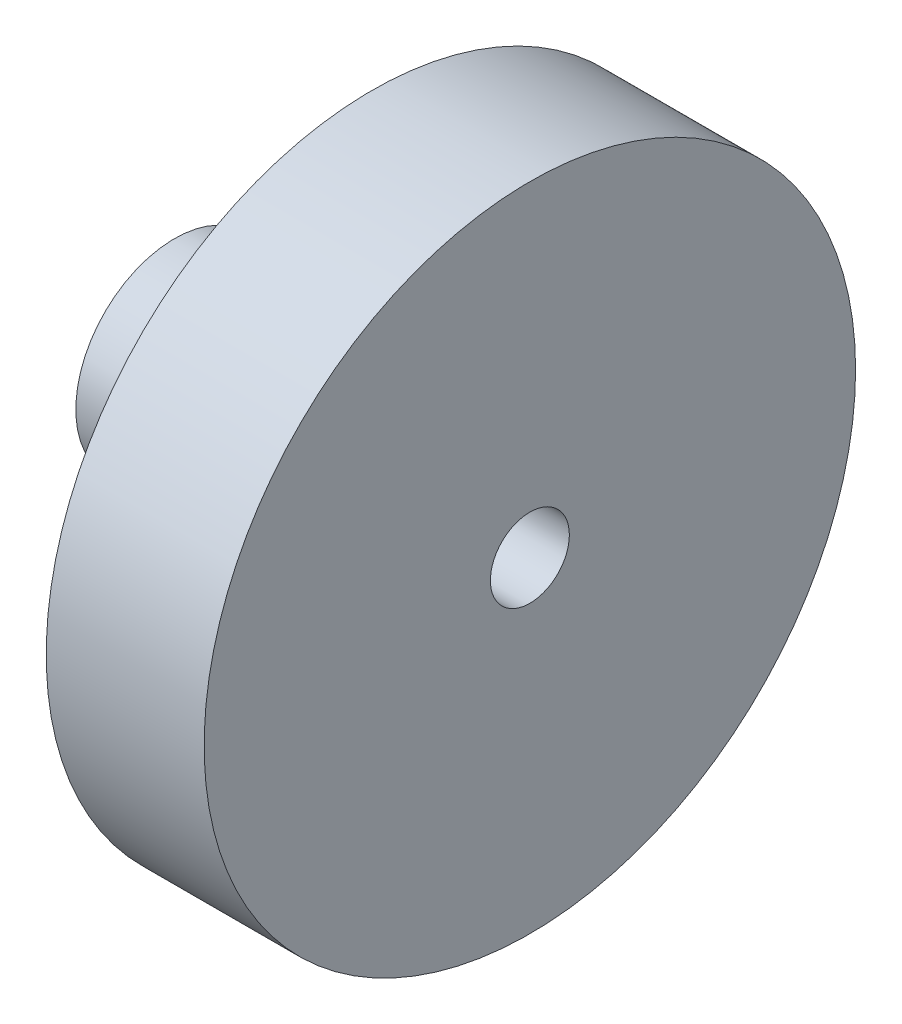
SolidWorks part; units mm, degrees
material "AISI 1020"
ref_plane "Plano frontal" through (0, 0, 0) normal (0, 0, 1) x (1, 0, 0)
ref_plane "Plano superior" through (0, 0, 0) normal (0, 1, 0) x (1, 0, 0)
ref_plane "Plano direito" through (0, 0, 0) normal (1, 0, 0) x (0, 0, -1)
sketch "Esboço3" plane through (0, 0, 0) normal (0, 0, 1) x (1, 0, 0)
  line L0 (0, 0) -> (-50.7324, 0) construction
  line L1 (0, 16.5) -> (0, 2)
  line L2 (0, 16.5) -> (-8, 16.5)
  line L3 (-8, 16.5) -> (-8, 5)
  line L4 (-8, 5) -> (-18, 5)
  line L5 (-18, 5) -> (-18, 2)
  line L6 (-18, 2) -> (0, 2)
  dimension "D1" = 2
  dimension "D2" = 16.5
  dimension "D3" = 8
  dimension "D4" = 10
  dimension "D5" = 5
revolve "Revolução1" add sketch "Esboço3" angle 360 about L0
ref_plane "Plano1" through (0, 5, 0) normal (0, 1, 0) x (1, 0, 0)
hole_wizard "Broca de rosquear para tarraxa de M2.2x0.451" positions "3DSketch6" profile "Esboço11" hole size "M2.2x0.45" standard "DIN"
sketch3d "3DSketch6"
  point P0 (-13.4532, 5, 0)
sketch "Esboço11" plane through (-13.4532, 5, 0) normal (1, 0, 0) x (0, 0, 1)
  line L0 (0, 0) -> (0, 3)
  line L1 (0, 3) -> (0.875, 3)
  line L2 (0.875, 3) -> (0.875, 0)
  line L5 (0.875, 0) -> (0, 0)
  line L11 (0, -6.35) -> (0, 107.95) construction
  dimension "Thru Hole Dia." = 1.75
  dimension "Thru Hole Depth" = 3
